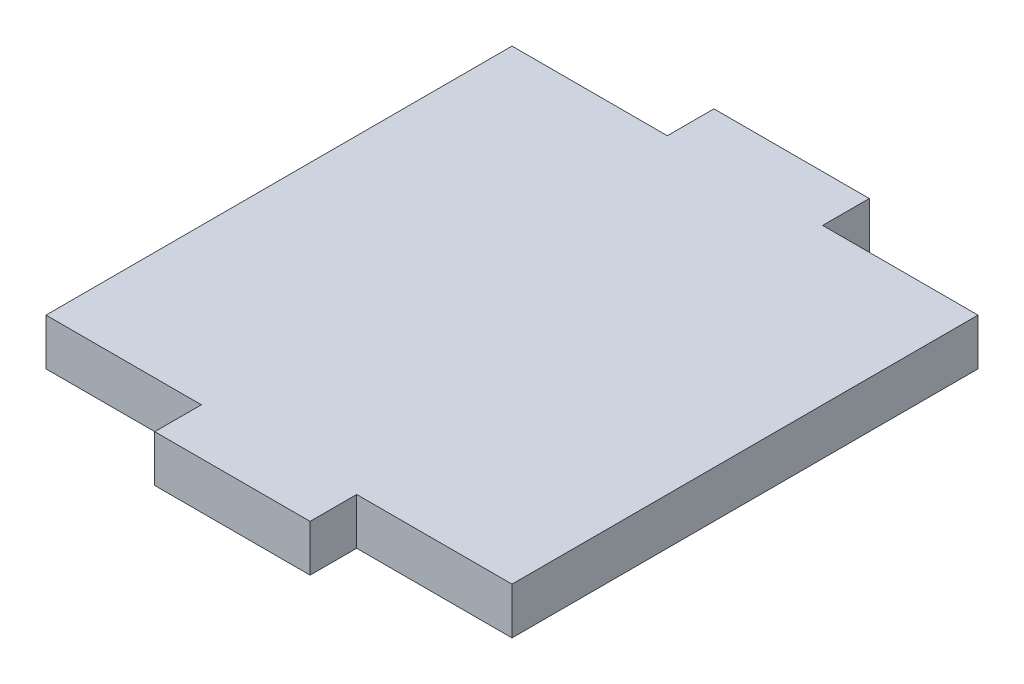
SolidWorks part; units mm, degrees
material "3mm Birch Ply Wood"
ref_plane "Front Plane" through (0, 0, 0) normal (0, 0, 1) x (1, 0, 0)
ref_plane "Top Plane" through (0, 0, 0) normal (0, 1, 0) x (1, 0, 0)
ref_plane "Right Plane" through (0, 0, 0) normal (1, 0, 0) x (0, 0, -1)
sketch "Sketch1" plane through (0, 0, 0) normal (0, 1, 0) x (1, 0, 0)
  line L0 (15, 0) -> (-15, 0) construction
  line L1 (-15, -15) -> (-5, -15)
  line L2 (-15, -15) -> (-15, 15)
  line L3 (-15, 15) -> (-5, 15)
  line L4 (15, -15) -> (15, 15)
  line L5 (-15, -15) -> (15, 15) construction
  line L6 (-15, 15) -> (15, -15) construction
  line L8 (5, 15) -> (5, 18)
  line L9 (5, 18) -> (-5, 18)
  line L10 (-5, 18) -> (-5, 15)
  line L13 (-5, -18) -> (-5, -15)
  line L14 (5, -18) -> (-5, -18)
  line L15 (5, -15) -> (5, -18)
  line L17 (5, 15) -> (15, 15)
  line L18 (5, -15) -> (15, -15)
  point P0 (0, 0)
  point P9 (0, 0)
extrude "Boss-Extrude1" add sketch "Sketch1" along normal blind 3
